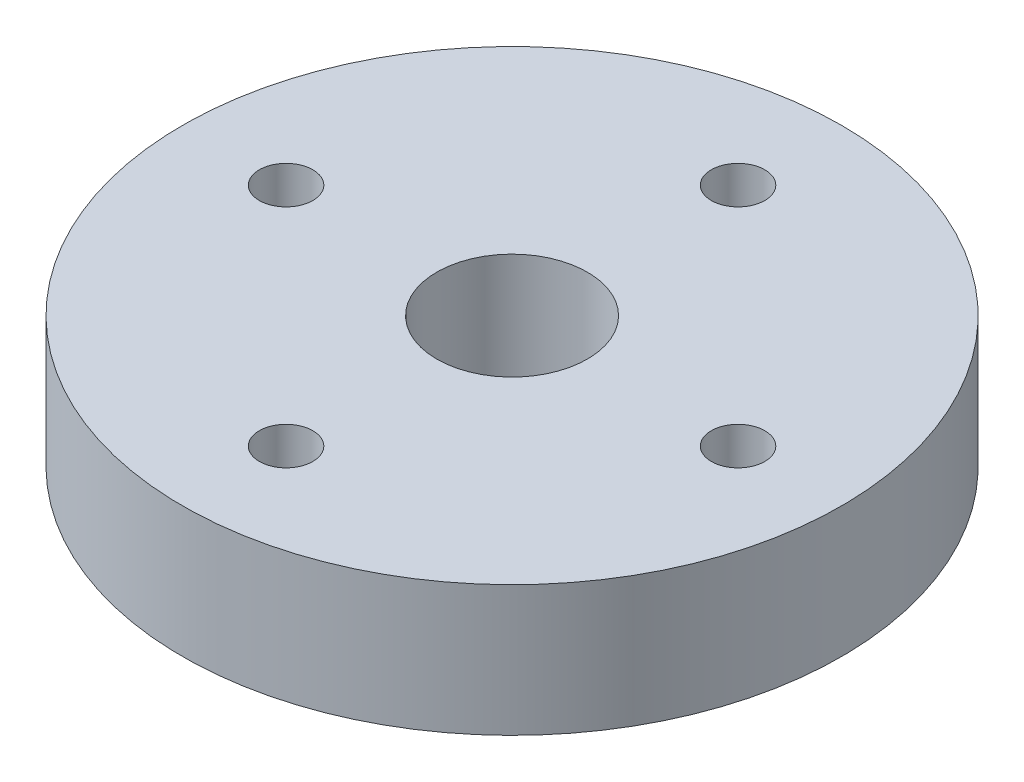
SolidWorks part; units mm, degrees
ref_plane "Front Plane" through (0, 0, 0) normal (0, 0, 1) x (1, 0, 0)
ref_plane "Top Plane" through (0, 0, 0) normal (0, 1, 0) x (1, 0, 0)
ref_plane "Right Plane" through (0, 0, 0) normal (1, 0, 0) x (0, 0, -1)
sketch "Sketch1" plane through (0, 0, 0) normal (0, 1, 0) x (1, 0, 0)
  circle A0 centre (0, 0) radius 17.5
  dimension "D1" = 35
extrude "Boss-Extrude1" add sketch "Sketch1" along normal blind 6.93
sketch "Sketch2" plane through (0, 6.93, 0) normal (0, 1, 0) x (1, 0, 0)
  line L0 (0, 0) -> (0, 18.4257) construction
  circle A0 centre (0, 12) radius 1.4188
  circle A1 centre (12, 0) radius 1.4188
  circle A2 centre (0, -12) radius 1.4188
  circle A3 centre (-12, 0) radius 1.4188
  point P14 (0, 0)
  dimension "D1" = 12
  dimension "D2" = 4
extrude "Cut-Extrude1" cut sketch "Sketch2" against normal through all
sketch "Sketch3" plane through (0, 6.93, 0) normal (0, 1, 0) x (1, 0, 0)
  circle A0 centre (0, 0) radius 4
  dimension "D1" = 8
extrude "Cut-Extrude2" cut sketch "Sketch3" against normal blind 6.93
